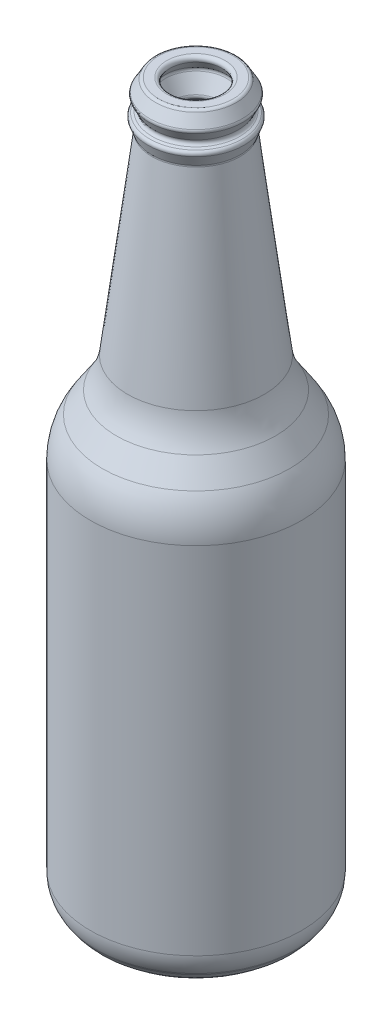
SolidWorks part; units mm, degrees
ref_plane "Front" through (0, 0, 0) normal (0, 0, 1) x (1, 0, 0)
ref_plane "Top" through (0, 0, 0) normal (0, 1, 0) x (1, 0, 0)
ref_plane "Right" through (0, 0, 0) normal (1, 0, 0) x (0, 0, -1)
sketch "Sketch3" plane through (0, 0, 0) normal (0, 0, 1) x (1, 0, 0)
  line L0 (0, 127.7917) -> (0, -135.8109) construction
  line L1 (11.1689, 127.7917) -> (13.5, 123.7917)
  line L2 (13.5, 123.7917) -> (11.5, 119.9167)
  line L3 (11.5, 119.9167) -> (14, 118.7917)
  line L4 (14, 118.7917) -> (12.5, 114.7917)
  line L5 (12.5, 114.7917) -> (20, 54.7917)
  line L6 (20, 54.7917) -> (30, 39.7917)
  line L7 (30, 39.7917) -> (30, -70.2083)
  line L8 (30, -70.2083) -> (25, -77.7083)
  line L9 (25, -77.7083) -> (0, -77.7083)
  line L10 (0, -77.7083) -> (0, 127.7917)
  line L11 (0, 127.7917) -> (11.1689, 127.7917)
  dimension "D1" = 13
  dimension "D2" = 13.5
  dimension "D3" = 14
  dimension "D4" = 4
  dimension "D5" = 9
  dimension "D6" = 12.5
  dimension "D7" = 11.5
  dimension "D8" = 60
  dimension "D9" = 15
  dimension "D10" = 20
  dimension "D11" = 110
  dimension "D12" = 30
  dimension "D13" = 7.5
  dimension "D14" = 25
revolve "Revolve1" add sketch "Sketch3" angle 360 about L0
shell "Shell1" thickness 4
fillet "Fillet1" radius 20 2 edges at (-30, 39.7917, 0) (-20, 54.7917, 0)
fillet "Fillet2" radius 10 2 edges at (-25, -77.7083, 0) (-30, -70.2083, 0)
fillet "Fillet3" radius 1 5 edges at (-12.5, 114.7917, 0) (-14, 118.7917, 0) (-11.5, 119.9167, 0) (-13.5, 123.7917, 0) (-11.1689, 127.7917, 0)
fillet "Fillet4" radius 1 3 edges at (-6.0099, 118.001, 0) (-8.9384, 123.675, 0) (6.5392, 127.7917, 0)
